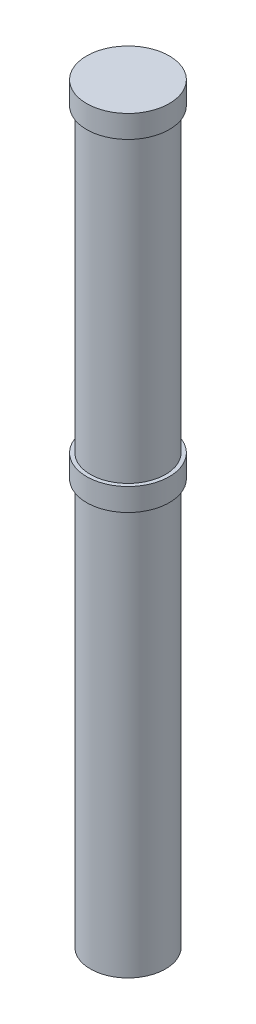
SolidWorks part; units mm, degrees
ref_plane "Front Plane" through (0, 0, 0) normal (0, 0, 1) x (1, 0, 0)
ref_plane "Top Plane" through (0, 0, 0) normal (0, 1, 0) x (1, 0, 0)
ref_plane "Right Plane" through (0, 0, 0) normal (1, 0, 0) x (0, 0, -1)
sketch "Sketch1" plane through (0, 0, 0) normal (0, 0, 1) x (1, 0, 0)
  line L1 (-4, -93.1993) -> (-5, -93.1993)
  line L2 (-5, -93.1993) -> (-5, -39.1993)
  line L3 (-5, -39.1993) -> (-5.5, -39.1993)
  line L4 (-5.5, -39.1993) -> (-5.5, -36.1993)
  line L5 (-5.5, -36.1993) -> (-5, -36.1993)
  line L6 (-5, -36.1993) -> (-5, 3.8007)
  line L7 (-5, 3.8007) -> (-5.5, 3.8007)
  line L8 (-5.5, 3.8007) -> (-5.5, 6.8007)
  line L9 (-5.5, 6.8007) -> (0, 6.8007)
  line L10 (0, 6.8007) -> (0, -68.1993)
  line L11 (0, -68.1993) -> (-4, -68.1993)
  line L12 (-4, -68.1993) -> (-4, -93.1993)
  dimension "D1" = 5
  dimension "D2" = 5.5
  dimension "D3" = 100
  dimension "D4" = 3
  dimension "D5" = 25
  dimension "D6" = 4
  dimension "D7" = 40
revolve "Revolve1" add sketch "Sketch1" angle 360 about L10
